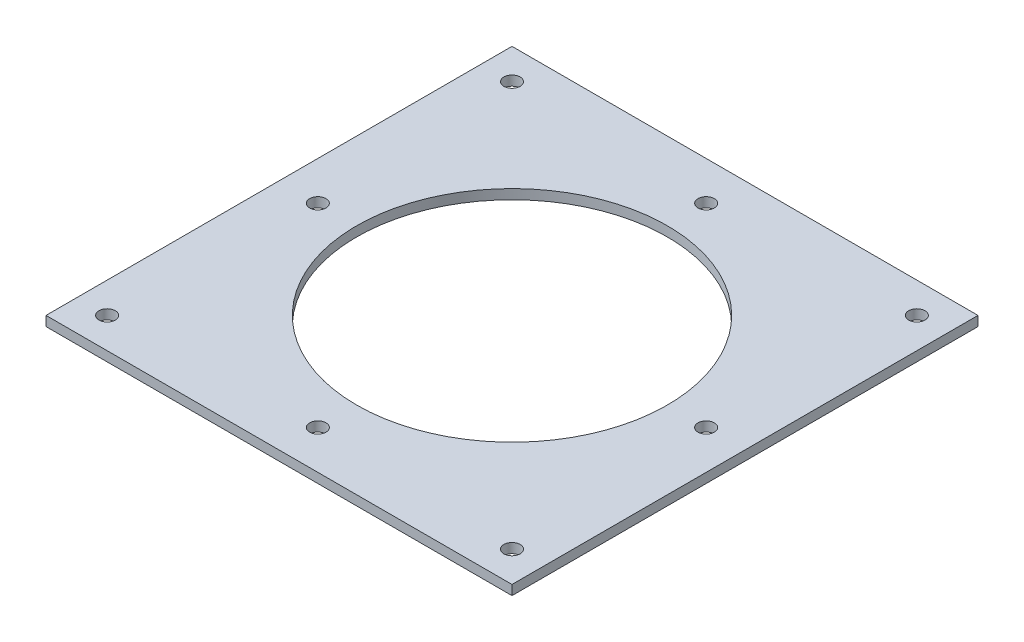
SolidWorks part; units mm, degrees
ref_plane "Front" through (0, 0, 0) normal (0, 0, 1) x (1, 0, 0)
ref_plane "Top" through (0, 0, 0) normal (0, 1, 0) x (1, 0, 0)
ref_plane "Right" through (0, 0, 0) normal (1, 0, 0) x (0, 0, -1)
sketch "Sketch2" plane through (0, 0, 0) normal (0, 1, 0) x (1, 0, 0)
  line L1 (-76.2, -76.2) -> (76.2, -76.2)
  line L2 (-76.2, -76.2) -> (-76.2, 76.2)
  line L3 (-76.2, 76.2) -> (76.2, 76.2)
  line L4 (76.2, -76.2) -> (76.2, 76.2)
  line L5 (-76.2, -76.2) -> (76.2, 76.2) construction
  line L6 (-76.2, 76.2) -> (76.2, -76.2) construction
  circle A0 centre (0, 0) radius 50.8
  point P0 (0, 0)
  dimension "D3" = 101.6
  dimension "D1" = 152.4
  dimension "D2" = 152.4
extrude "Boss-Extrude1" add sketch "Sketch2" along normal blind 3.175
sketch "Sketch3" plane through (0, 3.175, 0) normal (0, 1, 0) x (1, 0, 0)
  line L0 (0, 0) -> (0, -76.2) construction
  line L1 (-76.2, -76.2) -> (76.2, -76.2) construction
  line L2 (0, 0) -> (-76.2, 0) construction
  line L3 (-76.2, 76.2) -> (-76.2, -76.2) construction
  circle A0 centre (-66.2, -66.2) radius 2.665
  circle A1 centre (-66.2, 66.2) radius 2.665
  circle A2 centre (66.2, 66.2) radius 2.665
  circle A3 centre (66.2, -66.2) radius 2.665
  dimension "D1" = 5.33
  dimension "D3" = 10
  dimension "D2" = 10
extrude "Cut-Extrude1" cut sketch "Sketch3" against normal up to next
sketch "Sketch4" plane through (0, 3.175, 0) normal (0, 1, 0) x (1, 0, 0)
  circle A0 centre (0, 63.5) radius 2.665 construction
  circle A1 centre (-63.5, 0) radius 2.665 construction
  circle A2 centre (0, -63.5) radius 2.665 construction
  circle A3 centre (63.5, 0) radius 2.665 construction
  circle A4 centre (0, 63.5) radius 2.665
  circle A5 centre (-63.5, 0) radius 2.665
  circle A6 centre (0, -63.5) radius 2.665
  circle A7 centre (63.5, 0) radius 2.665
extrude "Cut-Extrude2" cut sketch "Sketch4" against normal up to next
